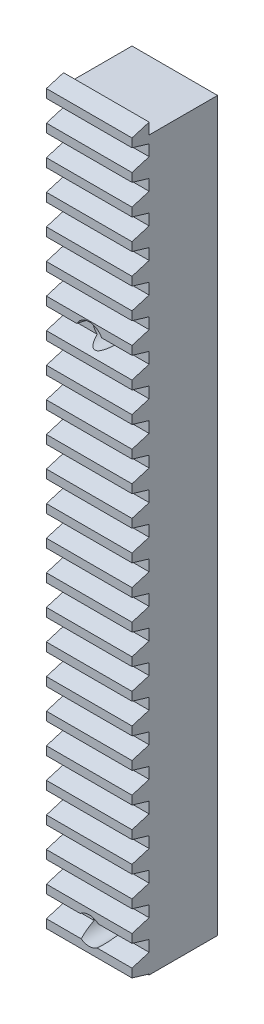
SolidWorks part; units mm, degrees
ref_plane "前视基准面" through (0, 0, 0) normal (0, 0, 1) x (1, 0, 0)
ref_plane "上视基准面" through (0, 0, 0) normal (0, 1, 0) x (1, 0, 0)
ref_plane "右视基准面" through (0, 0, 0) normal (1, 0, 0) x (0, 0, -1)
sketch "草图1" plane through (0, 0, 0) normal (1, 0, 0) x (0, 0, -1)
  line L1 (0, 42.5) -> (8, 42.5)
  line L2 (0, 42.5) -> (0, -42.5)
  line L3 (0, -42.5) -> (8, -42.5)
  line L4 (8, 42.5) -> (8, -42.5)
  dimension "D1" = 8
  dimension "D2" = 85
extrude "凸台-拉伸1" add sketch "草图1" along normal mid plane 10
sketch "草图2" plane through (0, 0, 0) normal (1, 0, 0) x (0, 0, -1)
  line L0 (0, -42.4) -> (-2, -41.8)
  line L1 (0, 42.5) -> (0, -42.5) construction
  line L2 (-2, -41.8) -> (-2, -40.8)
  line L3 (-2, -40.8) -> (0, -40.2)
  line L4 (-2, -41.3) -> (0.7599, -41.3) construction
  line L5 (0, -42.4) -> (0, -40.2)
  line L6 (0, -42.5) -> (8, -42.5) construction
  dimension "D1" = 1
  dimension "D2" = 2
  dimension "D3" = 2.2
  dimension "D4" = 1.2
extrude "凸台-拉伸2" add sketch "草图2" along normal mid plane 10
pattern_linear "阵列(线性)1" count 51 spacing 3.5 along (0, 1, 0) of "凸台-拉伸2"
sketch "草图3" plane through (0, 0, -8) normal (0, 0, -1) x (-1, 0, 0)
  line L0 (0, -42.5) -> (0, 42.5) construction
  line L1 (-5, -42.5) -> (5, -42.5) construction
  line L2 (-5, 42.5) -> (5, 42.5) construction
  line L3 (0, 20.5) -> (65.8116, 20.5) construction
  line L4 (-5, -42.5) -> (5, -42.5) construction
  circle A0 centre (0, -39.5) radius 1.6
  circle A1 centre (0, 20.5) radius 1.6
  circle A2 centre (0, 80.5) radius 1.6
  dimension "D1" = 120
  dimension "D2" = 3.2
  dimension "D3" = 3
extrude "切除-拉伸1" cut sketch "草图3" against normal through all
